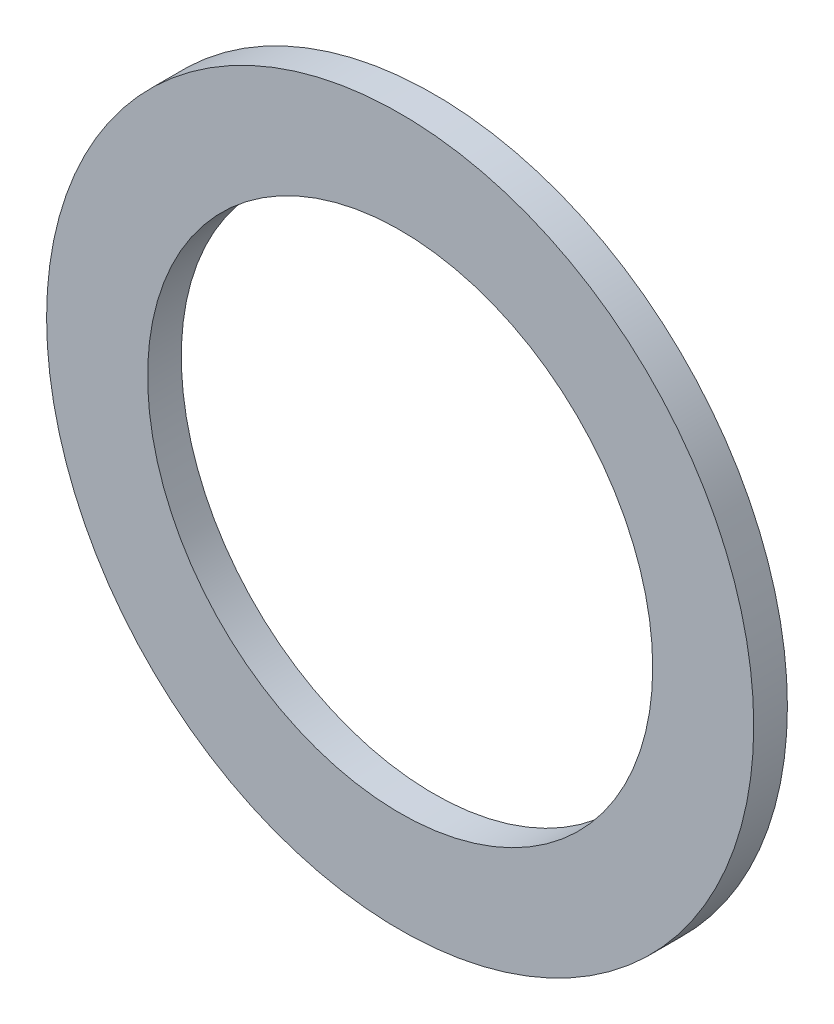
SolidWorks part; units mm, degrees
material "AISI 304"
ref_plane "前视基准面" through (0, 0, 0) normal (0, 0, 1) x (1, 0, 0)
ref_plane "上视基准面" through (0, 0, 0) normal (0, 1, 0) x (1, 0, 0)
ref_plane "右视基准面" through (0, 0, 0) normal (1, 0, 0) x (0, 0, -1)
other "Configuration Table"
sketch "草图1" plane through (0, 0, 0) normal (0, 0, 1) x (1, 0, 0)
  circle A0 centre (0, 0) radius 10.5
  circle A1 centre (0, 0) radius 7.5
  dimension "D1" = 21
  dimension "D2" = 15
extrude "凸台-拉伸1" add sketch "草图1" along normal blind 1
